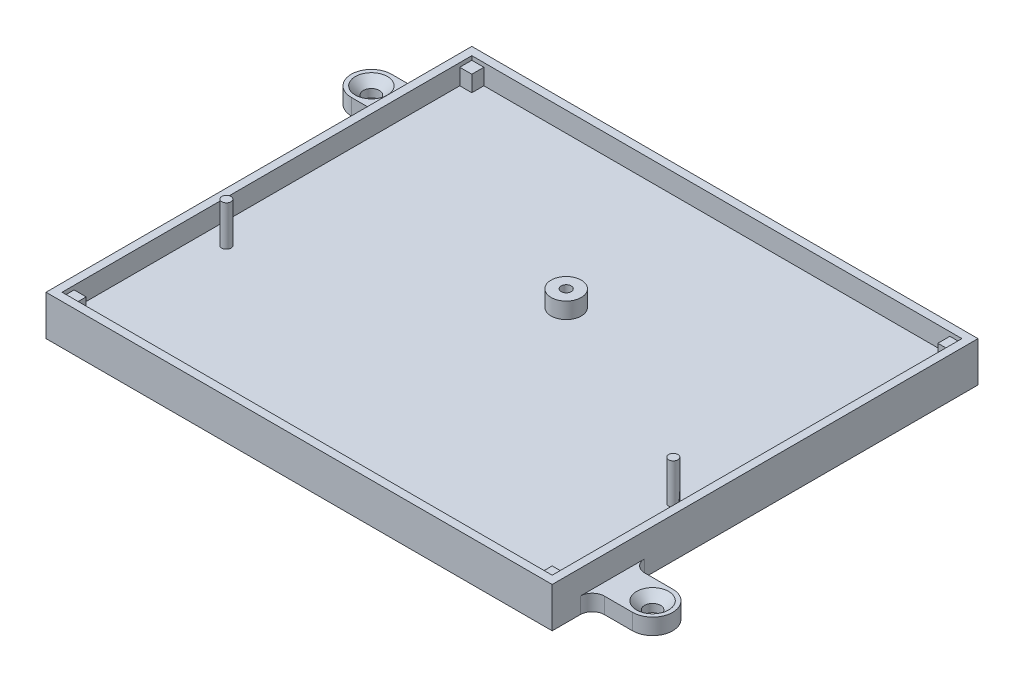
SolidWorks part; units mm, degrees
ref_plane "Front Plane" through (0, 0, 0) normal (0, 0, 1) x (1, 0, 0)
ref_plane "Top Plane" through (0, 0, 0) normal (0, 1, 0) x (1, 0, 0)
ref_plane "Right Plane" through (0, 0, 0) normal (1, 0, 0) x (0, 0, -1)
sketch "Sketch1" plane through (0, 0, 0) normal (0, 1, 0) x (1, 0, 0)
  line L1 (63, 53) -> (-63, 53)
  line L2 (63, 53) -> (63, -53)
  line L3 (63, -53) -> (-63, -53)
  line L4 (-63, 53) -> (-63, -53)
  line L5 (63, 53) -> (-63, -53) construction
  line L6 (63, -53) -> (-63, 53) construction
  point P0 (0, 0)
  dimension "D1" = 106
  dimension "D2" = 126
extrude "Boss-Extrude1" add sketch "Sketch1" along normal blind 5
sketch "Sketch3" plane through (0, 5, 0) normal (0, 1, 0) x (1, 0, 0)
  line L0 (-63, 53) -> (63, 53)
  line L1 (63, 53) -> (63, -53)
  line L2 (63, -53) -> (-63, -53)
  line L3 (-63, -53) -> (-63, 53)
  line L5 (61, -51) -> (-61, -51)
  line L6 (61, -51) -> (61, 51)
  line L7 (61, 51) -> (-61, 51)
  line L8 (-61, -51) -> (-61, 51)
  line L9 (61, -51) -> (-61, 51) construction
  line L10 (61, 51) -> (-61, -51) construction
  point P4 (0, 0)
  dimension "D1" = 2
  dimension "D2" = 2
extrude "Boss-Extrude3" add sketch "Sketch3" along normal blind 5
sketch "Sketch7" plane through (0, 0, 0) normal (0, 1, 0) x (1, 0, 0)
  line L0 (-63, 43) -> (-73, 43)
  line L1 (-63, 53) -> (-63, -53) construction
  line L2 (-73, 33) -> (-63, 33)
  line L3 (-63, 43) -> (-63, 33)
  line L4 (63, -33) -> (73, -33)
  line L5 (63, -53) -> (63, 53) construction
  line L6 (73, -43) -> (63, -43)
  line L7 (63, -43) -> (63, -33)
  line L8 (-63, -53) -> (63, -53) construction
  arc A0 (-73, 43) -> (-73, 33) centre (-73, 38) ccw
  arc A1 (73, -33) -> (73, -43) centre (73, -38) cw
  dimension "D1" = 10
  dimension "D2" = 10
  dimension "D3" = 10
  dimension "D4" = 10
  dimension "D5" = 10
  dimension "D6" = 10
extrude "Boss-Extrude5" add sketch "Sketch7" along normal blind 4
fillet "Fillet1" radius 3 4 edges at (-63, 2, -33) (-63, 2, -43) (63, 2, 43) (63, 2, 33)
hole_wizard "Ø4.0mm Dowel Hole1" positions "Sketch14" profile "Sketch15" hole size "Ø4.0" standard "ISO" end condition through all
sketch "Sketch14" plane through (0, 4, 0) normal (0, 1, 0) x (1, 0, 0)
  line L0 (-73, 43) -> (-73, 33) construction
  line L1 (73, -33) -> (73, -43) construction
  point P0 (-73, 38)
  point P9 (73, -38)
sketch "Sketch15" plane through (-73, 4, -38) normal (1, 0, 0) x (0, 0, 1)
  line L0 (0, 0) -> (0, 4)
  line L1 (0, 4) -> (2, 4)
  line L2 (2, 4) -> (2, 2)
  line L3 (2, 2) -> (4, 0)
  line L5 (4, 0) -> (0, 0)
  line L6 (-2, 2) -> (-4, 0) construction
  line L11 (0, -6.35) -> (0, 107.95) construction
  dimension "Thru Hole Dia." = 4
  dimension "Thru Hole Depth" = 4
  dimension "Near C'Sink Dia." = 8
  dimension "Near C'Sink Angle" = 90
sketch "Sketch17" plane through (0, 5, 0) normal (0, 1, 0) x (1, 0, 0)
  line L0 (-61, -51) -> (61, -51) construction
  line L2 (0, 0) -> (0, 21.9382) construction
  circle A0 centre (-55.626, -15.47) radius 1.15
  circle A1 centre (55.626, -15.47) radius 1.15
  dimension "D1" = 2.3
  dimension "D2" = 35.53
  dimension "D3" = 111.252
extrude "Boss-Extrude6" add sketch "Sketch17" along normal blind 10
sketch "Sketch4" plane through (0, 5, 0) normal (0, 1, 0) x (1, 0, 0)
  line L2 (0, 0) -> (0, 24.1725) construction
  circle A0 centre (0, 13.486) radius 3.75
  circle A1 centre (55.626, -15.47) radius 1.15 construction
  dimension "D1" = 7.5
  dimension "D2" = 28.956
sketch "Sketch18" plane through (0, 5, 0) normal (0, 1, 0) x (1, 0, 0)
  line L0 (0, 0) -> (0, 5.1135) construction
  line L1 (-61, 51) -> (-58, 51)
  line L2 (-61, 51) -> (-61, 48)
  line L3 (-61, 48) -> (-58, 48)
  line L4 (-58, 51) -> (-58, 48)
  line L5 (0, 0) -> (0, 24.1725) construction
  line L6 (58, 51) -> (58, 48)
  line L7 (61, 48) -> (58, 48)
  line L8 (61, 51) -> (61, 48)
  line L9 (61, 51) -> (58, 51)
  line L10 (0, 0) -> (9.5518, 0) construction
  line L11 (-58, -51) -> (-58, -48)
  line L12 (-61, -48) -> (-58, -48)
  line L13 (-61, -51) -> (-61, -48)
  line L14 (-61, -51) -> (-58, -51)
  line L15 (61, -51) -> (58, -51)
  line L16 (61, -51) -> (61, -48)
  line L17 (61, -48) -> (58, -48)
  line L18 (58, -51) -> (58, -48)
  dimension "D1" = 3
  dimension "D2" = 3
extrude "Boss-Extrude7" add sketch "Sketch18" along normal blind 4
extrude "Boss-Extrude8" add sketch "Sketch4" along normal blind 4
hole_wizard "Ø2.5mm Dowel Hole1" positions "Sketch19" profile "Sketch20" hole size "Ø2.5" standard "ISO" end condition through all
sketch "Sketch19" plane through (0, 9, 0) normal (0, 1, 0) x (1, 0, 0)
  point P0 (0, 13.486)
sketch "Sketch20" plane through (0, 9, -13.486) normal (1, 0, 0) x (0, 0, 1)
  line L0 (0, 0) -> (0, 9)
  line L1 (0, 9) -> (1.25, 9)
  line L2 (1.25, 9) -> (1.25, 0)
  line L5 (1.25, 0) -> (0, 0)
  line L11 (0, -6.35) -> (0, 107.95) construction
  dimension "Thru Hole Dia." = 2.5
  dimension "Thru Hole Depth" = 9
